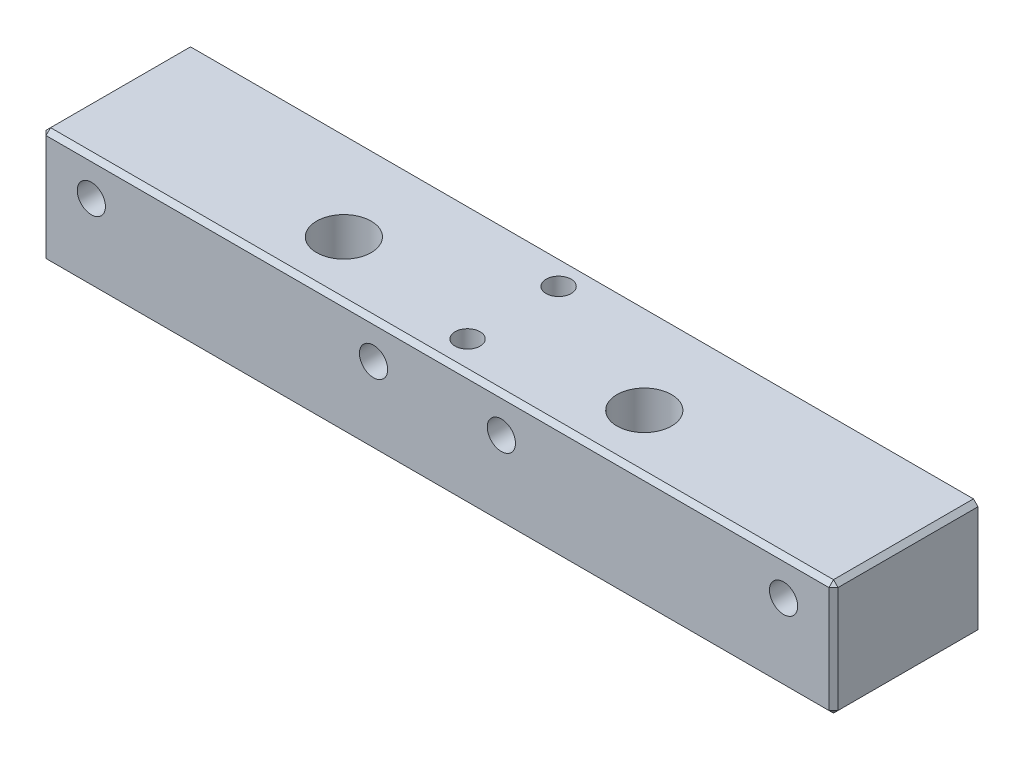
SolidWorks part; units mm, degrees
material "6061 Alloy"
ref_plane "Front Plane" through (0, 0, 0) normal (0, 0, 1) x (1, 0, 0)
ref_plane "Top Plane" through (0, 0, 0) normal (0, 1, 0) x (1, 0, 0)
ref_plane "Right Plane" through (0, 0, 0) normal (1, 0, 0) x (0, 0, -1)
sketch "Sketch1" plane through (0, 0, 0) normal (0, 0, 1) x (1, 0, 0)
  line L1 (-43.5, -6.35) -> (43.5, -6.35)
  line L2 (-43.5, -6.35) -> (-43.5, 6.35)
  line L3 (-43.5, 6.35) -> (43.5, 6.35)
  line L4 (43.5, -6.35) -> (43.5, 6.35)
  line L5 (-43.5, -6.35) -> (43.5, 6.35) construction
  line L6 (-43.5, 6.35) -> (43.5, -6.35) construction
  point P1 (0, 0)
  dimension "D1" = 87
  dimension "D2" = 12.7
extrude "Boss-Extrude1" add sketch "Sketch1" along normal mid plane 15.875
sketch "Sketch4" plane through (0, 6.35, 0) normal (0, 1, 0) x (1, 0, 0)
  line L1 (0, 3.845) -> (0, -8.155) construction
  line L2 (43.5, 7.9375) -> (-43.5, 7.9375) construction
  circle A0 centre (16.5, -1.7175) radius 3
  circle A1 centre (-16.5, -1.7175) radius 3
  dimension "D1" = 6
  dimension "D4" = 6
  dimension "D2" = 16.5
  dimension "D3" = 9.655
  dimension "D5" = 9.655
  dimension "D6" = 16.5
extrude "Cut-Extrude2" cut sketch "Sketch4" against normal through all
sketch "Sketch2" plane through (0, 0, 7.9375) normal (0, 0, 1) x (1, 0, 0)
  line L0 (0, 4.5) -> (0, -4.5) construction
  line L1 (-43.5, 2.35) -> (43.5, 2.35) construction
  line L2 (-43.5, 6.35) -> (-43.5, -6.35) construction
  line L3 (43.5, -6.35) -> (43.5, 6.35) construction
  line L4 (43.5, 6.35) -> (-43.5, 6.35) construction
  line L5 (-16.5, -6.35) -> (-16.5, 6.35) construction
  line L6 (16.5, -6.35) -> (16.5, 6.35) construction
  circle A0 centre (-38.02, 2.35) radius 1.55
  circle A1 centre (7.02, 2.35) radius 1.55
  circle A2 centre (-7.02, 2.35) radius 1.55
  circle A3 centre (38.02, 2.35) radius 1.55
  dimension "D1" = 31
  dimension "D3" = 3.1
  dimension "D4" = 9.48
  dimension "D2" = 31
  dimension "D5" = 4
  dimension "D6" = 9.48
extrude "Cut-Extrude1" cut sketch "Sketch2" against normal through all
chamfer "Chamfer3" distance 0.5 angle 45 8 edges at (43.5, 6.35, 0) (43.5, -6.35, 0) (-43.5, 6.35, 0) (-43.5, -6.35, 0) (43.5, 0, 7.9375) (0, 6.35, 7.9375) (0, -6.35, 7.9375) (-43.5, 0, 7.9375)
sketch "Sketch5" plane through (0, -6.35, 0) normal (0, 1, 0) x (1, 0, 0)
  line L0 (0, 7.9375) -> (0, -7.4375) construction
  line L1 (43, 7.9375) -> (-43, 7.9375) construction
  line L2 (-43, -7.4375) -> (43, -7.4375) construction
  line L3 (-43.5, -7.4375) -> (-43.5, 7.9375) construction
  line L4 (-37, 0.3675) -> (37, 0.3675) construction
  circle A0 centre (-37, 0.3675) radius 1.375
  circle A1 centre (0, 5.3675) radius 1.375
  circle A2 centre (37, 0.3675) radius 1.375
  circle A3 centre (0, -4.6325) radius 1.375
  dimension "D2" = 7.57
  dimension "D3" = 2.75
  dimension "D5" = 5
  dimension "D1" = 6.5
  dimension "D4" = 5
extrude "Cut-Extrude3" cut sketch "Sketch5" along normal blind 6
sketch "Sketch6" plane through (0, -6.35, 0) normal (0, -1, 0) x (1, 0, 0)
  circle A0 centre (0, 4.6325) radius 1.375
  circle A1 centre (0, -5.3675) radius 1.375
  circle A2 centre (0, 4.6325) radius 1.375 construction
  circle A3 centre (0, -5.3675) radius 1.375 construction
extrude "Cut-Extrude4" cut sketch "Sketch6" against normal through all
